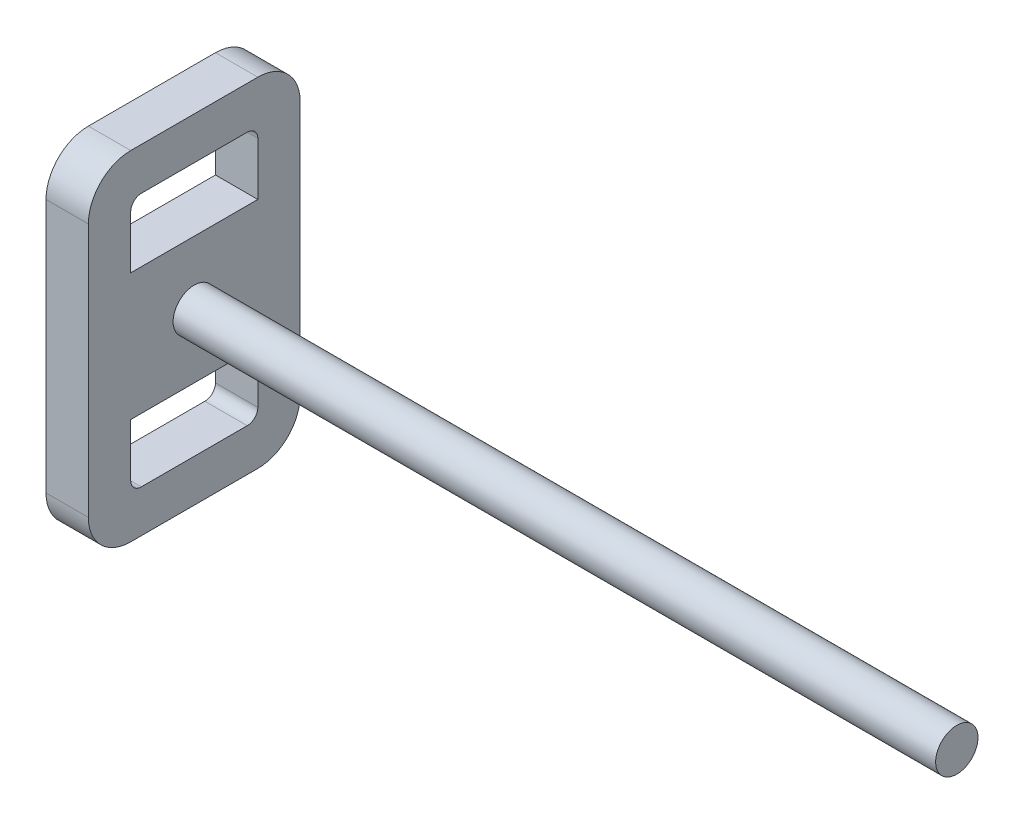
SolidWorks part; units mm, degrees
material "Custom Plastic"
ref_plane "X-Y Datum" through (0, 0, 0) normal (0, 0, 1) x (1, 0, 0)
ref_plane "X-Z Datum" through (0, 0, 0) normal (0, 1, 0) x (1, 0, 0)
ref_plane "Y-Z Datum" through (0, 0, 0) normal (1, 0, 0) x (0, 0, -1)
sketch "Sketch1" plane through (0, 0, 0) normal (1, 0, 0) x (0, 0, -1)
  circle A0 centre (0, 0) radius 12.7
  dimension "D1" = 25.4
extrude "Boss-Extrude1" add sketch "Sketch1" along normal blind 457.2
sketch "Sketch2" plane through (0, 0, 0) normal (-1, 0, 0) x (0, 0, 1)
  line L1 (-38.1, -101.6) -> (38.1, -101.6)
  line L2 (-63.5, -76.2) -> (-63.5, 76.2)
  line L3 (-38.1, 101.6) -> (38.1, 101.6)
  line L4 (63.5, -76.2) -> (63.5, 76.2)
  line L5 (-63.5, -101.6) -> (63.5, 101.6) construction
  line L6 (-63.5, 101.6) -> (63.5, -101.6) construction
  line L7 (31.75, 76.2) -> (-31.75, 76.2)
  line L8 (38.1, 69.85) -> (38.1, 38.1)
  line L9 (38.1, 38.1) -> (-38.1, 38.1)
  line L10 (-38.1, 69.85) -> (-38.1, 38.1)
  line L11 (31.75, -76.2) -> (-31.75, -76.2)
  line L12 (38.1, -69.85) -> (38.1, -38.1)
  line L13 (38.1, -38.1) -> (-38.1, -38.1)
  line L14 (-38.1, -69.85) -> (-38.1, -38.1)
  arc A0 (-63.5, 76.2) -> (-38.1, 101.6) centre (-38.1, 76.2) cw
  arc A1 (-38.1, -101.6) -> (-63.5, -76.2) centre (-38.1, -76.2) cw
  arc A2 (38.1, -101.6) -> (63.5, -76.2) centre (38.1, -76.2) ccw
  arc A3 (63.5, 76.2) -> (38.1, 101.6) centre (38.1, 76.2) ccw
  arc A4 (-31.75, -76.2) -> (-38.1, -69.85) centre (-31.75, -69.85) cw
  arc A5 (31.75, -76.2) -> (38.1, -69.85) centre (31.75, -69.85) ccw
  arc A6 (-38.1, 69.85) -> (-31.75, 76.2) centre (-31.75, 69.85) cw
  arc A7 (38.1, 69.85) -> (31.75, 76.2) centre (31.75, 69.85) ccw
  circle A8 centre (0, 0) radius 3.175
  point P0 (0, 0)
  dimension "D3" = 25.4
  dimension "D5" = 6.35
  dimension "D6" = 6.35
  dimension "D1" = 203.2
  dimension "D2" = 127
  dimension "D4" = 38.1
extrude "Boss-Extrude2" add sketch "Sketch2" along normal blind 25.4
sketch "Sketch3" plane through (-25.4, 0, 0) normal (-1, 0, 0) x (0, 0, 1)
  circle A0 centre (0, 0) radius 3.175
  dimension "D1" = 6.35
extrude "Cut-Extrude1" cut sketch "Sketch3" against normal blind 50.8
